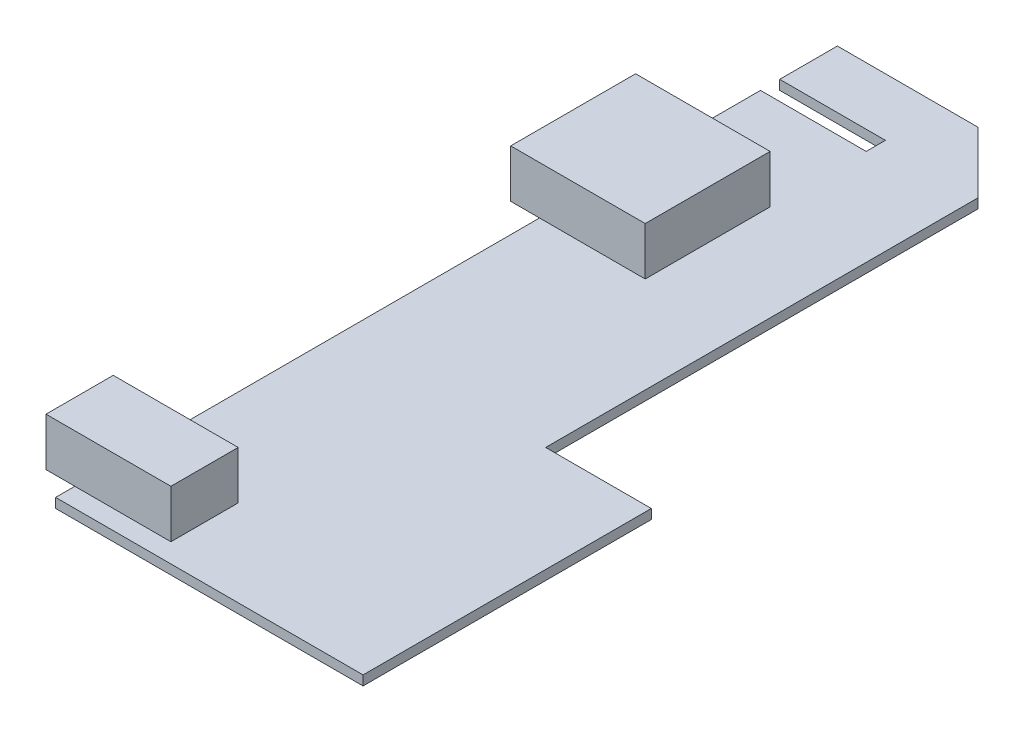
SolidWorks part; units mm, degrees
ref_plane "前基準面" through (0, 0, 0) normal (0, 0, 1) x (1, 0, 0)
ref_plane "上基準面" through (0, 0, 0) normal (0, 1, 0) x (1, 0, 0)
ref_plane "右基準面" through (0, 0, 0) normal (1, 0, 0) x (0, 0, -1)
sketch "草圖1" plane through (0, 0, 0) normal (0, 1, 0) x (1, 0, 0)
  line L0 (0, 0) -> (32, 0)
  line L1 (32, 0) -> (32, 30)
  line L2 (32, 30) -> (21, 30)
  line L3 (21, 30) -> (21, 75)
  line L4 (21, 75) -> (14.636, 81.364)
  line L5 (14.636, 81.364) -> (0, 81.364)
  line L6 (0, 81.364) -> (0, 75.364)
  line L7 (0, 75.364) -> (11, 75.364)
  line L8 (11, 75.364) -> (11, 73.364)
  line L9 (11, 73.364) -> (0, 73.364)
  line L10 (0, 73.364) -> (0, 0)
  dimension "D1" = 32
  dimension "D2" = 30
  dimension "D3" = 11
  dimension "D4" = 45
  dimension "D5" = 9
  dimension "D6" = 14.636
  dimension "D7" = 6
  dimension "D8" = 11
  dimension "D9" = 2
extrude "填料-伸長1" add sketch "草圖1" along normal blind 1
sketch "草圖2" plane through (0, 1, 0) normal (0, 1, 0) x (1, 0, 0)
  line L0 (-3, 9) -> (10, 9)
  line L1 (10, 9) -> (10, 2)
  line L2 (10, 2) -> (-3, 2)
  line L3 (-3, 2) -> (-3, 9)
  line L4 (0, 0) -> (32, 0) construction
  line L5 (0, 73.364) -> (0, 0) construction
  dimension "D1" = 7
  dimension "D2" = 13
  dimension "D3" = 2
  dimension "D4" = 10
extrude "填料-伸長2" add sketch "草圖2" along normal blind 5
sketch "草圖3" plane through (0, 1, 0) normal (0, 1, 0) x (1, 0, 0)
  line L0 (-3, 63.364) -> (-3, 50.364)
  line L1 (-3, 50.364) -> (11, 50.364)
  line L2 (11, 50.364) -> (11, 63.364)
  line L3 (-3, 63.364) -> (11, 63.364)
  line L4 (11, 73.364) -> (0, 73.364) construction
  line L5 (0, 73.364) -> (0, 9) construction
  dimension "D1" = 13
  dimension "D2" = 14
  dimension "D3" = 10
  dimension "D4" = 11
extrude "填料-伸長3" add sketch "草圖3" along normal blind 5
